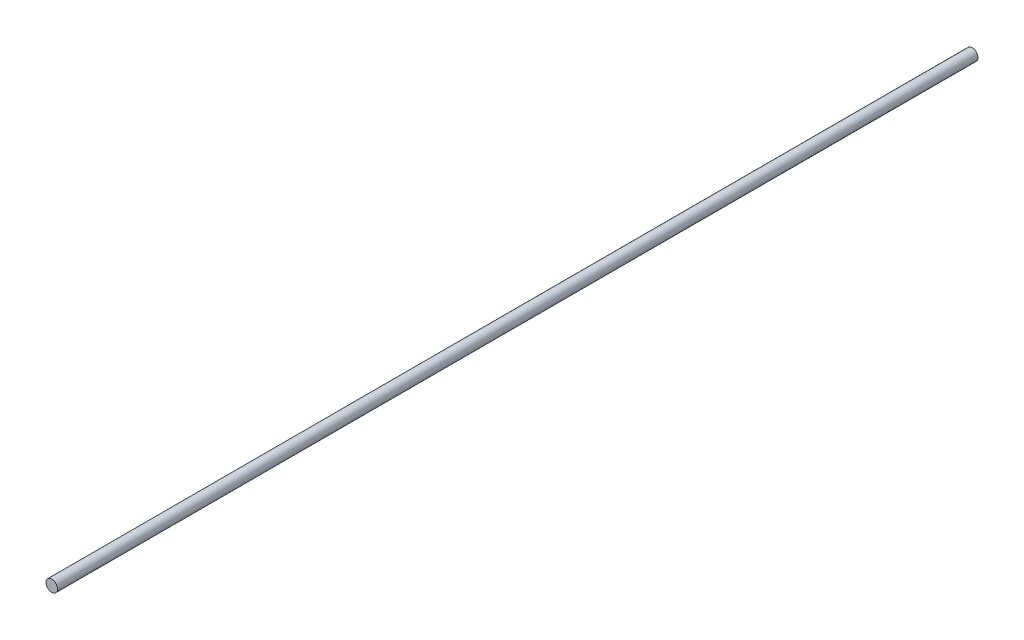
SolidWorks part; units mm, degrees
ref_plane "Plan de face" through (0, 0, 0) normal (0, 0, 1) x (1, 0, 0)
ref_plane "Plan de dessus" through (0, 0, 0) normal (0, 1, 0) x (1, 0, 0)
ref_plane "Plan de droite" through (0, 0, 0) normal (1, 0, 0) x (0, 0, -1)
sketch "Esquisse1" plane through (0, 0, 0) normal (0, 0, 1) x (1, 0, 0)
  circle A0 centre (0, 0) radius 5
  dimension "D1" = 10
extrude "Boss.-Extru.1" add sketch "Esquisse1" along normal blind 800
